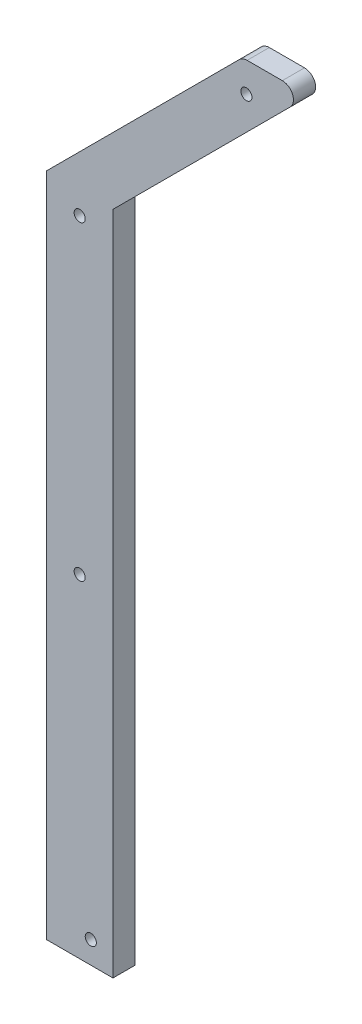
SolidWorks part; units mm, degrees
ref_plane "Front Plane" through (0, 0, 0) normal (0, 0, 1) x (1, 0, 0)
ref_plane "Top Plane" through (0, 0, 0) normal (0, 1, 0) x (1, 0, 0)
ref_plane "Right Plane" through (0, 0, 0) normal (1, 0, 0) x (0, 0, -1)
sketch "Sketch1" plane through (0, 0, 0) normal (0, 0, 1) x (1, 0, 0)
  line L0 (-19.05, 190.5) -> (91.3433, 300.8933)
  line L1 (-19.05, -190.5) -> (19.05, -190.5)
  line L2 (-19.05, -190.5) -> (-19.05, 190.5)
  line L3 (-19.05, 190.5) -> (19.05, 190.5)
  line L4 (19.05, -190.5) -> (19.05, 190.5)
  line L5 (-19.05, -190.5) -> (19.05, 190.5) construction
  line L6 (-19.05, 190.5) -> (19.05, -190.5) construction
  line L7 (19.05, 190.5) -> (120.4631, 291.9131)
  line L8 (115.9729, 302.7532) -> (95.8335, 302.7532)
  arc A0 (91.3433, 300.8933) -> (95.8335, 302.7532) centre (95.8335, 296.4032) cw
  arc A1 (120.4631, 291.9131) -> (115.9729, 302.7532) centre (115.9729, 296.4032) ccw
  point P0 (0, 0)
  point P10 (93.2032, 302.7532)
  dimension "D4" = 6.35
  dimension "D1" = 38.1
  dimension "D2" = 381
  dimension "D3" = 158.75
extrude "Boss-Extrude2" add sketch "Sketch1" along normal blind 12.7 contours L1 L4 L3 L2 | L7 A1 L8 A0 L0 L3
sketch "Sketch2" plane through (0, 0, 12.7) normal (0, 0, 1) x (1, 0, 0)
  line L0 (-19.05, -190.5) -> (19.05, -190.5) construction
  line L1 (19.05, -190.5) -> (19.05, 190.5) construction
  circle A0 centre (6.35, -177.8) radius 3.175
  dimension "D1" = 12.7
  dimension "D2" = 12.7
sketch "Sketch3" plane through (0, 0, 12.7) normal (0, 0, 1) x (1, 0, 0)
  circle A0 centre (95.3967, 285.7618) radius 3.175
extrude "Cut-Extrude3" cut sketch "Sketch3" against normal blind 863.6 contours A0
sketch "Sketch4" plane through (0, 0, 12.7) normal (0, 0, 1) x (1, 0, 0)
  circle A0 centre (0, 0) radius 3.175
extrude "Cut-Extrude4" cut sketch "Sketch4" against normal blind 36
extrude "Cut-Extrude5" cut sketch "Sketch2" against normal blind 52.578
sketch "Sketch5" plane through (0, 0, 12.7) normal (0, 0, 1) x (1, 0, 0)
  line L0 (-19.05, 190.5) -> (19.05, 190.5) construction
  circle A0 centre (0, 177.8) radius 3.175
  dimension "D1" = 12.7
extrude "Cut-Extrude6" cut sketch "Sketch5" against normal blind 148.082
